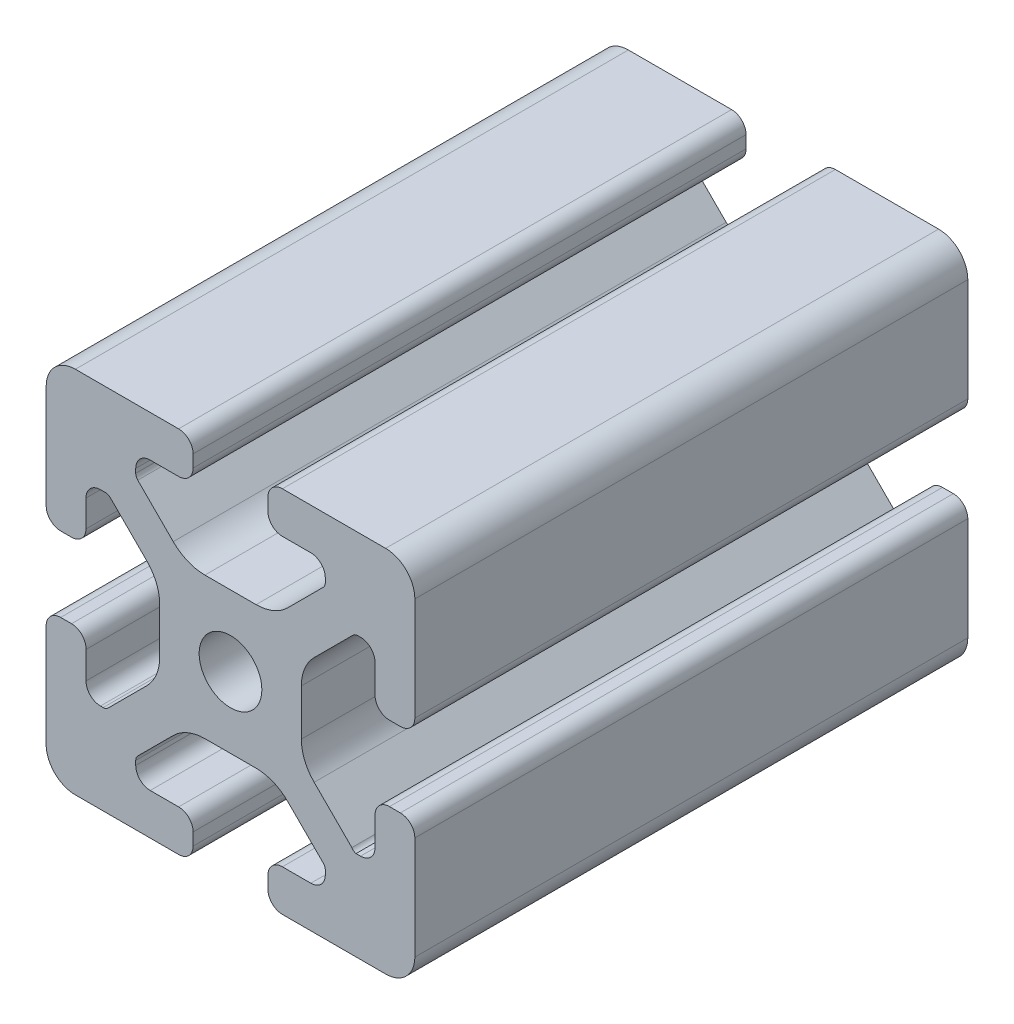
SolidWorks part; units mm, degrees
material "6061 Alloy"
ref_plane "Front Plane" through (0, 0, 0) normal (0, 0, 1) x (1, 0, 0)
ref_plane "Top Plane" through (0, 0, 0) normal (0, 1, 0) x (1, 0, 0)
ref_plane "Right Plane" through (0, 0, 0) normal (1, 0, 0) x (0, 0, -1)
sketch "Sketch1" plane through (0, 0, 0) normal (0, 0, 1) x (1, 0, 0)
  line L0 (0, 19.7407) -> (0, -19.7407) construction
  line L1 (19.0335, 0) -> (-20.7246, 0) construction
  line L2 (-8.715, -15.5246) -> (-5.63, -15.5246)
  line L3 (-10.285, -13.9546) -> (-10.285, -13.4925)
  line L4 (-6.2171, -9.1098) -> (-10.0624, -12.9551)
  line L5 (2.7773, -7.685) -> (-2.7773, -7.685)
  line L6 (10.0624, -12.9551) -> (6.2171, -9.1098)
  line L7 (10.285, -13.9546) -> (10.285, -13.4925)
  line L8 (5.63, -15.5246) -> (8.715, -15.5246)
  line L9 (4.06, -18.43) -> (4.06, -17.0946)
  line L10 (-4.06, -18.43) -> (-4.06, -17.0946)
  line L11 (15.68, -8.7154) -> (15.68, -5.63)
  line L12 (-14.11, -10.2854) -> (-13.8169, -10.2854)
  line L13 (20, -16.83) -> (20, -5.63)
  line L14 (20, 5.63) -> (20, 13.0011)
  line L15 (-16.83, 20) -> (-5.63, 20)
  line L16 (5.63, 20) -> (12.9796, 20)
  line L18 (-8.715, 15.5246) -> (-5.63, 15.5246)
  line L19 (-20, -17.0184) -> (-20, -5.7579)
  line L20 (-20, 5.573) -> (-20, 13.0045)
  line L21 (-15.68, -8.7154) -> (-15.68, -5.7579)
  line L23 (-16.6746, -20) -> (-5.63, -20)
  line L24 (5.63, -20) -> (13, -20)
  line L53 (14.11, -10.2854) -> (13.6201, -10.2854)
  line L54 (13.1637, -9.947) -> (9.0762, -5.8595)
  line L55 (7.685, -2.5008) -> (7.685, 2.5008)
  line L56 (9.0762, 5.8595) -> (13.2795, 10.0628)
  line L57 (13.8169, 10.2854) -> (14.11, 10.2854)
  line L58 (15.68, 8.7154) -> (15.68, 5.63)
  line L59 (17.25, 4.06) -> (18.43, 4.06)
  line L61 (20, 13.0011) -> (20, 16.83)
  line L62 (16.83, 20) -> (12.9796, 20)
  line L64 (4.06, 18.43) -> (4.06, 17.0946)
  line L65 (5.63, 15.5246) -> (8.715, 15.5246)
  line L66 (10.285, 13.9546) -> (10.285, 13.4925)
  line L67 (10.0624, 12.9551) -> (6.2171, 9.1098)
  line L68 (2.7773, 7.685) -> (-2.7773, 7.685)
  line L69 (-6.2171, 9.1098) -> (-10.0624, 12.9551)
  line L70 (-10.285, 13.4925) -> (-10.285, 13.9546)
  line L72 (-4.06, 17.0946) -> (-4.06, 18.43)
  line L75 (-20, 16.83) -> (-20, 13.0045)
  line L77 (-18.43, 4.003) -> (-17.25, 4.003)
  line L78 (-15.68, 5.573) -> (-15.68, 8.4757)
  line L79 (-14.0552, 10.0447) -> (-13.7199, 10.033)
  line L80 (-13.0405, 9.8238) -> (-9.0762, 5.8595)
  line L81 (-7.685, 2.5008) -> (-7.685, -2.5008)
  line L82 (-9.0762, -5.8595) -> (-13.2795, -10.0628)
  line L85 (-17.25, -4.1204) -> (-18.43, -4.1204)
  line L100 (13, -20) -> (16.83, -20)
  line L103 (18.43, -4.06) -> (17.25, -4.06)
  arc A0 (-5.63, -15.5246) -> (-4.06, -17.0946) centre (-5.63, -17.0946) cw
  arc A1 (-8.715, -15.5246) -> (-10.285, -13.9546) centre (-8.715, -13.9546) cw
  arc A2 (-10.285, -13.4925) -> (-10.0624, -12.9551) centre (-9.525, -13.4925) cw
  arc A3 (-6.2171, -9.1098) -> (-2.7773, -7.685) centre (-2.7773, -12.5496) cw
  arc A4 (2.7773, -7.685) -> (6.2171, -9.1098) centre (2.7773, -12.5496) cw
  arc A5 (10.0624, -12.9551) -> (10.285, -13.4925) centre (9.525, -13.4925) cw
  arc A6 (10.285, -13.9546) -> (8.715, -15.5246) centre (8.715, -13.9546) cw
  arc A7 (4.06, -17.0946) -> (5.63, -15.5246) centre (5.63, -17.0946) cw
  arc A8 (5.63, -20) -> (4.06, -18.43) centre (5.63, -18.43) cw
  arc A9 (-4.06, -18.43) -> (-5.63, -20) centre (-5.63, -18.43) cw
  circle A45 centre (0, 0) radius 3.4
  arc A46 (17.25, -4.06) -> (15.68, -5.63) centre (17.25, -5.63) ccw
  arc A47 (14.11, -10.2854) -> (15.68, -8.7154) centre (14.11, -8.7154) ccw
  arc A48 (13.1637, -9.947) -> (13.6201, -10.2854) centre (13.8117, -9.55) ccw
  arc A49 (7.685, -2.5008) -> (9.0762, -5.8595) centre (12.435, -2.5008) ccw
  arc A50 (9.0762, 5.8595) -> (7.685, 2.5008) centre (12.435, 2.5008) ccw
  arc A51 (13.8169, 10.2854) -> (13.2795, 10.0628) centre (13.8169, 9.5254) ccw
  arc A52 (15.68, 8.7154) -> (14.11, 10.2854) centre (14.11, 8.7154) ccw
  arc A53 (15.68, 5.63) -> (17.25, 4.06) centre (17.25, 5.63) ccw
  arc A54 (18.43, 4.06) -> (20, 5.63) centre (18.43, 5.63) ccw
  arc A55 (20, 16.83) -> (16.83, 20) centre (16.83, 16.83) ccw
  arc A56 (5.63, 20) -> (4.06, 18.43) centre (5.63, 18.43) ccw
  arc A57 (4.06, 17.0946) -> (5.63, 15.5246) centre (5.63, 17.0946) ccw
  arc A58 (10.285, 13.9546) -> (8.715, 15.5246) centre (8.715, 13.9546) ccw
  arc A59 (10.0624, 12.9551) -> (10.285, 13.4925) centre (9.525, 13.4925) ccw
  arc A60 (2.7773, 7.685) -> (6.2171, 9.1098) centre (2.7773, 12.5496) ccw
  arc A61 (-6.2171, 9.1098) -> (-2.7773, 7.685) centre (-2.7773, 12.5496) ccw
  arc A62 (-10.285, 13.4925) -> (-10.0624, 12.9551) centre (-9.525, 13.4925) ccw
  arc A63 (-8.715, 15.5246) -> (-10.285, 13.9546) centre (-8.715, 13.9546) ccw
  arc A64 (-5.63, 15.5246) -> (-4.06, 17.0946) centre (-5.63, 17.0946) ccw
  arc A65 (-4.06, 18.43) -> (-5.63, 20) centre (-5.63, 18.43) ccw
  arc A66 (-16.83, 20) -> (-20, 16.83) centre (-16.83, 16.83) ccw
  arc A67 (-20, 5.573) -> (-18.43, 4.003) centre (-18.43, 5.573) ccw
  arc A68 (-17.25, 4.003) -> (-15.68, 5.573) centre (-17.25, 5.573) ccw
  arc A69 (-14.0552, 10.0447) -> (-15.68, 8.4757) centre (-14.11, 8.4757) ccw
  arc A70 (-13.0405, 9.8238) -> (-13.7199, 10.033) centre (-13.5779, 9.2864) ccw
  arc A71 (-7.685, 2.5008) -> (-9.0762, 5.8595) centre (-12.435, 2.5008) ccw
  arc A72 (-9.0762, -5.8595) -> (-7.685, -2.5008) centre (-12.435, -2.5008) ccw
  arc A73 (-13.8169, -10.2854) -> (-13.2795, -10.0628) centre (-13.8169, -9.5254) ccw
  arc A74 (-15.68, -8.7154) -> (-14.11, -10.2854) centre (-14.11, -8.7154) ccw
  arc A75 (-15.68, -5.7579) -> (-17.25, -4.1204) centre (-17.2485, -5.6904) ccw
  arc A76 (-18.43, -4.1204) -> (-20, -5.7579) centre (-18.4315, -5.6904) ccw
  arc A77 (-20, -17.0184) -> (-16.6746, -20) centre (-16.8354, -16.8341) ccw
  arc A88 (16.83, -20) -> (20, -16.83) centre (16.83, -16.83) ccw
  arc A89 (20, -5.63) -> (18.43, -4.06) centre (18.43, -5.63) ccw
  dimension "D2" = 6.8
  dimension "D7" = 20.57
  dimension "D1" = 40
  dimension "D3" = 4.32
  dimension "D4" = 15.37
  dimension "D5" = 20
  dimension "D6" = 4.32
  dimension "D9" = 15.37
extrude "Extrude1" add sketch "Sketch1" against normal blind 60
equation "\"PinDiameter\"= 1cm"
equation "\"WallThickness\"= 0.5cm"
equation "\"BottomPlateX\"= 100cm"
equation "\"BottomPlateZ\"= 60cm"
equation "\"BottomPlateHoleD\"=((\"ArmPlateX\")^2+(\"ArmPlateDepth\")^2)^.5+ 10mm"
equation "\"ActuatorL\"= 35cm"
equation "\"ActuatorPinD\"= 6mm"
equation "\"ActuatorPinL\"= 13cm"
equation "\"Box-X\"= 40cm"
equation "\"Box-Z\"= 20cm"
equation "\"Box-Y\"= 30cm"
equation "\"ArmPlateThickness\"= 1cm"
equation "\"ArmPlateX\"= 40cm"
equation "\"ArmPlateDepth\"= 20cm"
equation "\"Arm1X\"= 5cm"
equation "\"Arm1L\"= 60cm"
equation "\"Arm2GAP\"= 5cm"
equation "\"Arm2L\"= 60cm"
equation "\"Arm2H\"= 5cm"
equation "\"Arm2Extension\"= 5cm"
equation "\"Arm3GAP\"= 5cm"
equation "\"Arm3L\"= 60cm"
equation "\"Arm3H\"= 5cm"
equation "\"Pin1-2L\"= \"Arm2GAP\" + (2 * \"WallThickness\")"
equation "\"Pin2-3L\"= \"Arm3GAP\" + (4 * \"WallThickness\")"
equation "\"DCMotor1D\"= 65mm"
equation "\"DCMotor1L\"= 20cm"
equation "\"DCMotor1ShaftL\"= \"ArmPlateThickness\" + 1.7cm"
equation "\"DCMotor2X\"= 57mm"
equation "\"DCMotor2D\"= 57mm"
equation "\"DCMotor2L\"= 153mm"
equation "\"DCMotor2ShaftL\"= 34mm"
equation "\"DCMotor2ShaftD\"= 14mm"
equation "\"BenchDepth\"= 5cm"
equation "\"BenchH\"= 10cm"
equation "\"BenchL\"= 15cm"
equation "\"PillowBlockW\"= 5cm"
equation "\"PillowBlockCenterH\"= \"DCMotor2X\"/2"
equation "\"EncoderRadius\"= 19mm"
equation "\"EncoderShaftL\"= 15mm"
equation "\"EncoderL\"= 33mm"
equation "\"EncoderHousingThickness\"= 7.5mm"
equation "\"TurntableID\"= 70mm"
equation "\"TurntableInner2*t\" = (\"TurntableOD\"-\"TurntableID\")*.25 - .5mm"
equation "\"TurntableInnerHoleRadius\"= \"TurntableID\"*.5 + \"TurntableInner2*t\"*.5"
equation "\"TurntableOD\"= 120mm"
equation "\"TurntableOuterHoleRadius\" = \"TurntableOD\"*.5 - ((\"TurntableOD\"-\"TurntableID\")*.25-.5mm)*.5"
equation "\"4040Height\" = 30cm"
equation "\"LENGTH@Extrude1\"=\"TurntableOD\"+2cm-80mm"
